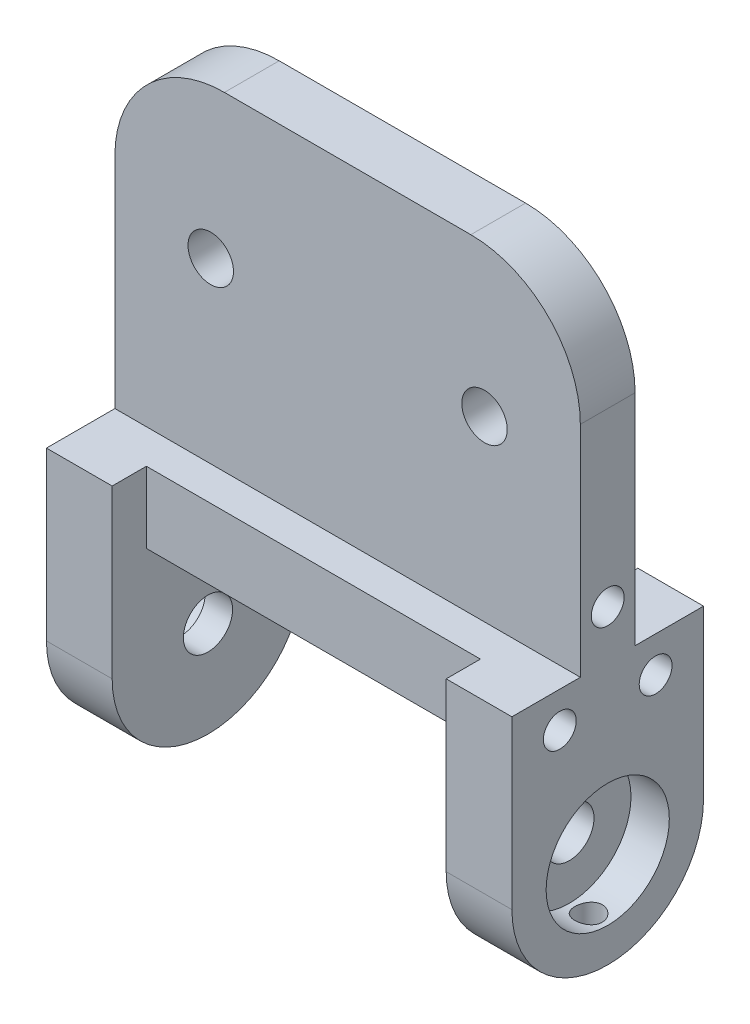
SolidWorks part; units mm, degrees
ref_plane "Front Plane" through (0, 0, 0) normal (0, 0, 1) x (1, 0, 0)
ref_plane "Top Plane" through (0, 0, 0) normal (0, 1, 0) x (1, 0, 0)
ref_plane "Right Plane" through (0, 0, 0) normal (1, 0, 0) x (0, 0, -1)
sketch "Sketch1" plane through (0, 0, 0) normal (0, 1, 0) x (1, 0, 0)
  line L1 (42.5, 5) -> (-42.5, 5)
  line L2 (42.5, 5) -> (42.5, -5)
  line L3 (42.5, -5) -> (-42.5, -5)
  line L4 (-42.5, 5) -> (-42.5, -5)
  line L5 (42.5, 5) -> (-42.5, -5) construction
  line L6 (42.5, -5) -> (-42.5, 5) construction
  point P0 (0, 0)
  dimension "D1" = 10
  dimension "D2" = 85
extrude "Boss-Extrude1" add sketch "Sketch1" along normal blind 60
sketch "Sketch2" plane through (0, 0, 5) normal (0, 0, 1) x (1, 0, 0)
  line L0 (-42.5, 60) -> (42.5, 60) construction
  line L2 (-25, 32.5) -> (25, 32.5) construction
  line L3 (-42.5, 7.5) -> (42.5, 7.5) construction
  line L4 (-42.5, 60) -> (-42.5, 0) construction
  line L5 (42.5, 60) -> (42.5, 0) construction
  line L6 (0, 7.5) -> (0, 0) construction
  circle A1 centre (-25, 32.5) radius 4.15
  circle A2 centre (25, 32.5) radius 4.15
  circle A3 centre (-25, 32.5) radius 25 construction
  circle A4 centre (25, 32.5) radius 25 construction
  point P4 (0, 32.5)
  point P5 (0, 60)
  dimension "D1" = 50
  dimension "D2" = 8.3
  dimension "D3" = 7.5
extrude "Cut-Extrude1" cut sketch "Sketch2" against normal through all
sketch "Sketch3" plane through (0, 0, 0) normal (0, -1, 0) x (1, 0, 0)
  line L1 (-42.5, 17.5) -> (42.5, 17.5)
  line L2 (-42.5, 17.5) -> (-42.5, -17.5)
  line L3 (-42.5, -17.5) -> (42.5, -17.5)
  line L4 (42.5, 17.5) -> (42.5, -17.5)
  line L9 (-42.5, -5) -> (-42.5, 5) construction
  line L10 (42.5, 5) -> (42.5, -5) construction
  point P8 (-42.5, 0)
  point P9 (42.5, 0)
  dimension "D2" = 35
extrude "Boss-Extrude2" add sketch "Sketch3" along normal blind 13
sketch "Sketch4" plane through (-42.5, 0, 0) normal (-1, 0, 0) x (0, 0, 1)
  line L0 (17.5, -13) -> (-17.5, -13) construction
  line L1 (-17.5, -13) -> (-17.5, -30.5)
  line L2 (-17.5, -13) -> (17.5, -13)
  line L3 (17.5, -13) -> (17.5, -30.5)
  line L4 (17.5, -13) -> (17.5, 0) construction
  line L5 (-17.5, -13) -> (-17.5, 0) construction
  circle A0 centre (0, -30.5) radius 11.25
  arc A1 (-17.5, -30.5) -> (17.5, -30.5) centre (0, -30.5) ccw
  arc A2 (-17.5, -30.5) -> (17.5, -30.5) centre (0, -30.5) cw construction
  point P0 (0, -19.25)
  dimension "D1" = 22.5
extrude "Boss-Extrude4" add sketch "Sketch4" against normal blind 12
sketch "Sketch5" plane through (-30.5, 0, 0) normal (1, 0, 0) x (0, 0, -1)
  circle A0 centre (0, -30.5) radius 11.25 construction
  circle A1 centre (0, -30.5) radius 11.25
  circle A2 centre (0, -30.5) radius 4.5
  dimension "D1" = 4.5
extrude "Boss-Extrude5" add sketch "Sketch5" against normal blind 5
sketch "Sketch6" plane through (-42.5, 0, 0) normal (-1, 0, 0) x (0, 0, 1)
  line L0 (-17.5, 0) -> (-17.5, -13) construction
  line L1 (-17.5, -30.5) -> (-17.5, 0) construction
  line L2 (-17.5, -6.5) -> (17.5, -6.5) construction
  line L3 (17.5, -30.5) -> (17.5, 0) construction
  line L4 (-17.5, 0) -> (0, -13) construction
  line L5 (0, -13) -> (17.5, 0) construction
  line L6 (-8.75, -6.5) -> (0, 8.6554) construction
  line L7 (0, 8.6554) -> (8.75, -6.5) construction
  circle A0 centre (-8.75, -6.5) radius 3
  circle A1 centre (8.75, -6.5) radius 3
  circle A2 centre (0, 8.6554) radius 3
  dimension "D1" = 6
  dimension "D2" = 60
extrude "Cut-Extrude2" cut sketch "Sketch6" against normal blind 10
mirror "Mirror2" about plane through (0, 0, 0) normal (1, 0, 0) of "Cut-Extrude2", "Boss-Extrude4", "Boss-Extrude5"
ref_plane "Plane1" through (0, -48, 0) normal (0, -1, 0) x (-1, 0, 0)
sketch "Sketch7" plane through (0, -48, 0) normal (0, -1, 0) x (-1, 0, 0)
  line L0 (39, 0) -> (-39, 0) construction
  line L2 (-42.5, 17.5) -> (-42.5, -17.5) construction
  line L3 (-35.5, -17.5) -> (-35.5, 17.5) construction
  line L4 (-42.5, 17.5) -> (-42.5, -17.5) construction
  line L5 (-42.5, 17.5) -> (-35.5, -17.5) construction
  line L6 (-35.5, 11.25) -> (-35.5, -11.25) construction
  line L7 (-35.5, 11.25) -> (-35.5, -11.25) construction
  circle A0 centre (-39, 0) radius 2.5
  circle A1 centre (39, 0) radius 2.5
  point P8 (0, 0)
  dimension "D1" = 2.5
extrude "Cut-Extrude3" cut sketch "Sketch7" against normal blind 10
fillet "Fillet2" radius 20 2 edges at (-42.5, 60, 0) (42.5, 60, 0)
sketch "Sketch8" plane through (0, -13, 0) normal (0, -1, 0) x (1, 0, 0)
  line L0 (-30.5, 17.5) -> (30.5, 17.5)
  line L1 (30.5, 17.5) -> (30.5, 11.25)
  line L2 (30.5, 17.5) -> (30.5, -17.5) construction
  line L3 (30.5, 11.25) -> (-30.5, 11.25)
  line L4 (-30.5, 17.5) -> (-30.5, -17.5) construction
  line L5 (-30.5, 11.25) -> (-30.5, 17.5)
  line L6 (-30.5, -17.5) -> (-30.5, -11.25)
  line L7 (-30.5, -17.5) -> (30.5, -17.5) construction
  line L8 (-30.5, -11.25) -> (30.5, -11.25)
  line L9 (30.5, -11.25) -> (30.5, -17.5)
  line L10 (30.5, -17.5) -> (-30.5, -17.5)
  line L11 (42.5, -17.5) -> (42.5, -5) construction
  line L12 (42.5, -17.5) -> (42.5, -5) construction
  point P19 (42.5, -11.25)
extrude "Cut-Extrude4" cut sketch "Sketch8" against normal blind 20
sketch "Sketch10" plane through (-42.5, 0, 0) normal (-1, 0, 0) x (0, 0, 1)
  line L0 (12.9098, -30.5) -> (-12.9098, -30.5) construction
  line L2 (-17.5, -30.5) -> (-11.25, -30.5) construction
  circle A0 centre (-12.9098, -30.5) radius 0.9306
  circle A1 centre (12.9098, -30.5) radius 0.9306
  circle A2 centre (0, -30.5) radius 11.25 construction
  circle A3 centre (0, -30.5) radius 11.25
  point P11 (0, -30.5)
sketch "Sketch11" plane through (-42.5, 0, 0) normal (-1, 0, 0) x (0, 0, 1)
  line L1 (-5, 60) -> (-4, 60)
  line L2 (-5, 60) -> (-5, 20)
  line L3 (-5, 20) -> (-4, 20)
  line L4 (-4, 60) -> (-4, 20)
  line L5 (5, 60) -> (4, 60)
  line L6 (5, 60) -> (5, 20)
  line L7 (5, 20) -> (4, 20)
  line L8 (4, 60) -> (4, 20)
  dimension "D1" = 1
  dimension "D2" = 20
extrude "Cut-Extrude5" [suppressed] cut sketch "Sketch11" against normal through all
